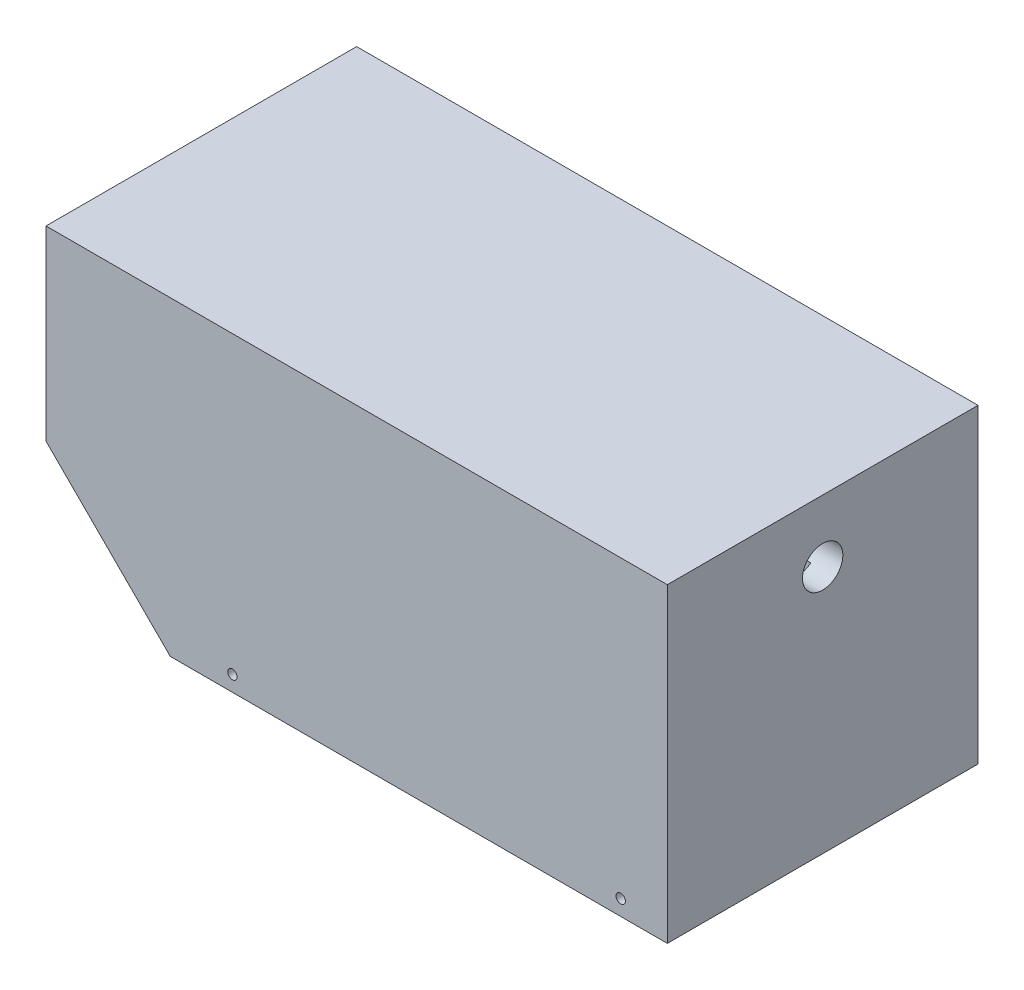
SolidWorks part; units mm, degrees
material "ABS"
ref_plane "Plan de face" through (0, 0, 0) normal (0, 0, 1) x (1, 0, 0)
ref_plane "Plan de dessus" through (0, 0, 0) normal (0, 1, 0) x (1, 0, 0)
ref_plane "Plan de droite" through (0, 0, 0) normal (1, 0, 0) x (0, 0, -1)
sketch "Esquisse1" plane through (0, 0, 0) normal (0, 0, 1) x (1, 0, 0)
  line L1 (100, -50) -> (-100, -50)
  line L2 (100, -50) -> (100, 50)
  line L3 (100, 50) -> (-100, 50)
  line L4 (-100, -50) -> (-100, 50)
  line L5 (100, -50) -> (-100, 50) construction
  line L6 (100, 50) -> (-100, -50) construction
  point P0 (0, 0)
  dimension "D1" = 200
  dimension "D2" = 100
extrude "Boss.-Extru.1" add sketch "Esquisse1" along normal blind 100
chamfer "Chanfrein1" distance 40 angle 45 1 edges at (-100, -50, 50)
sketch "Esquisse2" plane through (100, 0, 0) normal (1, 0, 0) x (0, 0, -1)
  line L0 (-100, 50) -> (0, 50) construction
  line L1 (0, -50) -> (0, 50) construction
  circle A0 centre (-50, 30) radius 6.5
  dimension "D1" = 13
  dimension "D2" = 20
  dimension "D3" = 50
extrude "Enlèv. mat.-Extru.1" cut sketch "Esquisse2" against normal through all
sketch "Esquisse4" plane through (0, 0, 100) normal (0, 0, 1) x (1, 0, 0)
  line L0 (100, -50) -> (100, 50) construction
  line L1 (-60, -50) -> (100, -50) construction
  circle A0 centre (85, -45) radius 1.5
  circle A1 centre (-40, -45) radius 1.5
  dimension "D1" = 3
  dimension "D2" = 15
  dimension "D3" = 5
  dimension "D4" = 140
extrude "Enlèv. mat.-Extru.3" cut sketch "Esquisse4" against normal through all
sketch "Esquisse5" plane through (0, -50, 0) normal (0, -1, 0) x (1, 0, 0)
  line L0 (-60, 100) -> (-60, 0) construction
  line L1 (-52, 8) -> (92, 8)
  line L2 (-52, 8) -> (-52, 92)
  line L3 (-52, 92) -> (92, 92)
  line L4 (92, 8) -> (92, 92)
  line L5 (100, 100) -> (100, 0) construction
  line L7 (-60, 100) -> (100, 100) construction
  line L9 (-60, 0) -> (100, 0) construction
  dimension "D1" = 8
  dimension "D2" = 8
  dimension "D3" = 8
  dimension "D4" = 8
extrude "Enlèv. mat.-Extru.4" cut sketch "Esquisse5" against normal blind 75
sketch "Esquisse6" plane through (0, -50, 0) normal (0, -1, 0) x (1, 0, 0)
  line L0 (-60, 100) -> (-60, 0) construction
  line L1 (-56, 4) -> (96, 4)
  line L2 (-56, 4) -> (-56, 96)
  line L3 (-56, 96) -> (96, 96)
  line L4 (96, 4) -> (96, 96)
  line L5 (100, 100) -> (100, 0) construction
  line L6 (-60, 0) -> (100, 0) construction
  line L7 (-60, 100) -> (100, 100) construction
  dimension "D1" = 4
  dimension "D2" = 4
  dimension "D3" = 4
  dimension "D4" = 4
extrude "Enlèv. mat.-Extru.5" cut sketch "Esquisse6" against normal blind 8
